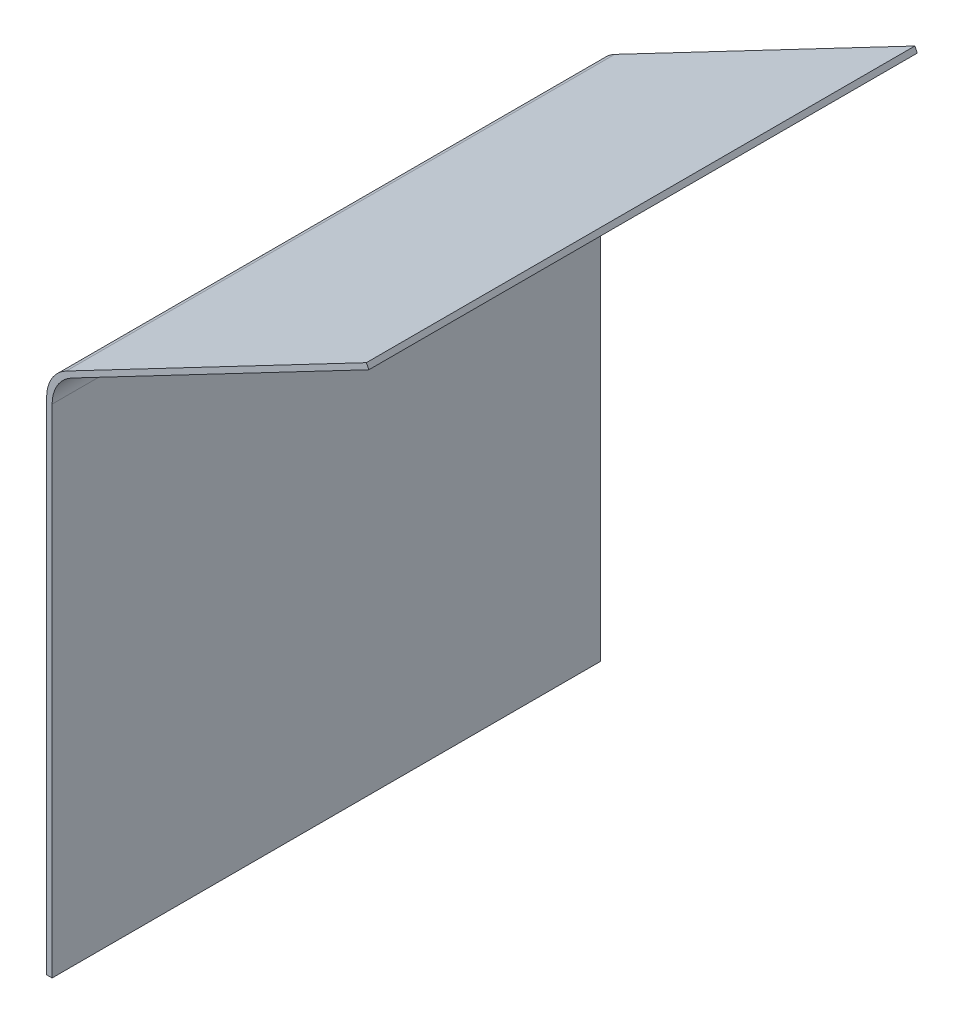
SolidWorks part; units mm, degrees
ref_plane "Front Plane" through (0, 0, 0) normal (0, 0, 1) x (1, 0, 0)
ref_plane "Top Plane" through (0, 0, 0) normal (0, 1, 0) x (1, 0, 0)
ref_plane "Right Plane" through (0, 0, 0) normal (1, 0, 0) x (0, 0, -1)
sketch "Sketch1" plane through (0, 0, 0) normal (0, 0, 1) x (1, 0, 0)
  line L1 (-168.636, -331.05) -> (-168.636, -59.1988)
  line L5 (4.6335, 43.7193) -> (-157.921, -41.4847)
  line L6 (-156.6291, -40.8076) -> (-21.841, 29.8426)
  line L7 (-21.841, 29.8426) -> (4.6335, 43.7193)
  line L8 (-171.636, -331.05) -> (-171.636, -57.3842)
  line L9 (3.2407, 46.3764) -> (-160.921, -39.6701)
  line L10 (4.6335, 43.7193) -> (-168.636, -47.1011) construction
  line L11 (-168.636, -365.115) -> (-168.636, -47.1011) construction
  line L12 (3.2407, 46.3764) -> (-170.0287, -44.444) construction
  line L13 (-171.636, -365.115) -> (-171.636, -47.1011) construction
  line L14 (3.2407, 46.3764) -> (4.6335, 43.7193)
  line L17 (-170.3777, -331.05) -> (-168.636, -331.05)
  line L19 (-171.636, -331.05) -> (-170.3777, -331.05)
  arc A0 (-157.921, -41.4847) -> (-168.636, -59.1988) centre (-148.636, -59.1988) ccw
  arc A1 (-160.921, -39.6701) -> (-171.636, -57.3842) centre (-151.636, -57.3842) ccw
  point P18 (-179.9777, -341.05)
  point P19 (-170.3777, -341.05)
  dimension "D3" = 20
  dimension "D4" = 20
  dimension "D1" = 3
  dimension "D2" = 3
extrude "Boss-Extrude1" add sketch "Sketch1" along normal blind 280 and the other way blind 20
